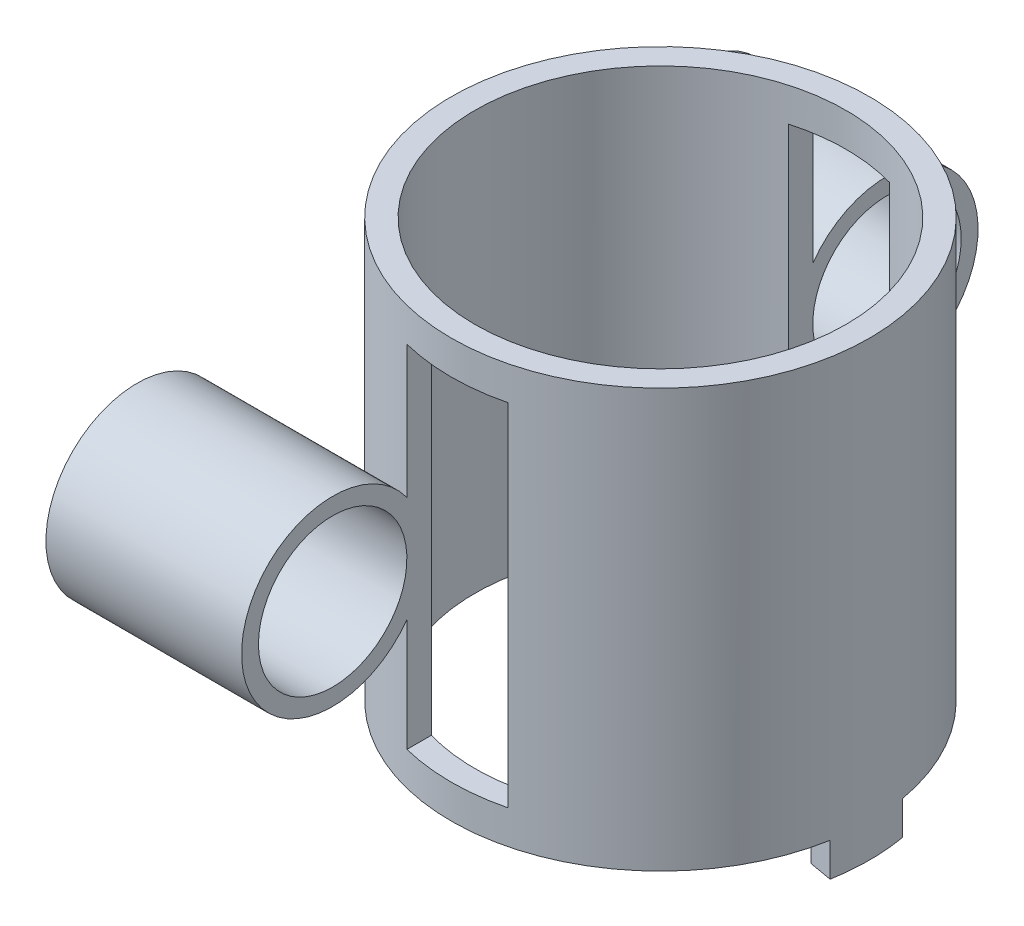
SolidWorks part; units mm, degrees
ref_plane "Alzado" through (0, 0, 0) normal (0, 0, 1) x (1, 0, 0)
ref_plane "Planta" through (0, 0, 0) normal (0, 1, 0) x (1, 0, 0)
ref_plane "Vista lateral" through (0, 0, 0) normal (1, 0, 0) x (0, 0, -1)
sketch "Sketch1" plane through (0, 0, 0) normal (0, 1, 0) x (1, 0, 0)
  circle A0 centre (0, 0) radius 31
  circle A1 centre (0, 0) radius 27.5
  dimension "D1" = 62
  dimension "D2" = 55
extrude "Boss-Extrude1" add sketch "Sketch1" along normal blind 62
sketch "Sketch6" plane through (0, 0, 0) normal (0, -1, 0) x (1, 0, 0)
  line L0 (27.5, 0) -> (32.5, 0)
  line L1 (27.0822, 4.7753) -> (32.0063, 5.6436)
  line L2 (27.0822, -4.7753) -> (32.0063, -5.6436)
  arc A0 (32.0063, -5.6436) -> (32.0063, 5.6436) centre (0, 0) ccw
  arc A1 (27.0822, -4.7753) -> (27.0822, 4.7753) centre (0, 0) ccw
  circle M5 centre (0, 0) radius 31
  circle M6 centre (0, 0) radius 27.5
  dimension "D1" = 55
  dimension "D2" = 65
  dimension "D3" = 10
extrude "Boss-Extrude3" add sketch "Sketch6" along normal blind 5 contours L2 L0 M6 M5 | L1 L0 M6 M5
sketch "Sketch8" plane through (0, 0, 0) normal (0, 0, 1) x (1, 0, 0)
  line L0 (-31, 62) -> (-31, 0) construction
  line L1 (-7.5, 57) -> (7.5, 57)
  line L2 (-7.5, 57) -> (-7.5, 5)
  line L3 (-7.5, 5) -> (7.5, 5)
  line L4 (7.5, 57) -> (7.5, 5)
  line L5 (31, 62) -> (-31, 62) construction
  line L7 (-31, 0) -> (30.529, 0) construction
  dimension "D1" = 7.5
  dimension "D2" = 5
  dimension "D3" = 15
  dimension "D4" = 5
extrude "Cut-Extrude1" cut sketch "Sketch8" against normal through all and the other way through all
ref_plane "Plane1" through (-7.5, 0, 0) normal (1, 0, 0) x (0, 0, -1)
sketch "Sketch9" plane through (-7.5, 0, 0) normal (1, 0, 0) x (0, 0, -1)
  line L2 (30.0791, 23.4768) -> (30.0791, 21.6738)
  line L7 (30.0791, 37.3262) -> (30.0791, 45)
  line L8 (30.0791, 57) -> (26.4575, 57) construction
  line L9 (30.0791, 57) -> (30.0791, 5) construction
  circle A0 centre (41.0791, 29.5) radius 11
  circle A1 centre (41.0791, 29.5) radius 13.5
  dimension "D4" = 22
  dimension "D6" = 27
  dimension "D1" = 27.5
  dimension "D2" = 11
extrude "Boss-Extrude4" add sketch "Sketch9" against normal up to surface (26 mm away)
sketch "Sketch10" plane through (-33.5, 0, 0) normal (-1, 0, 0) x (0, 0, 1)
  circle A0 centre (-41.0791, 29.5) radius 13.5
  circle A1 centre (-41.0791, 29.5) radius 13.5 construction
extrude "Boss-Extrude5" add sketch "Sketch10" along normal blind 3
ref_plane "Plane2" through (-17.2856, -28.4484, -28.838) normal (0, 0, 1) x (1, 0, 0)
sketch "Sketch12" plane through (-17.2856, -28.4484, -28.838) normal (0, 0, 1) x (1, 0, 0)
  line L0 (9.7856, 71.4484) -> (-19.2144, 71.4484) construction
  line L1 (-19.2144, 71.4484) -> (-19.2144, 44.4484) construction
  circle A0 centre (-14.2144, 57.9484) radius 1.5
  dimension "D2" = 3
  dimension "D1" = 13.5
  dimension "D3" = 5
extrude "Cut-Extrude2" cut sketch "Sketch12" against normal blind 3
mirror "Mirror1" about plane through (0, 0, 0) normal (0, 0, 1) of "Cut-Extrude2", "Boss-Extrude5", "Boss-Extrude4"
